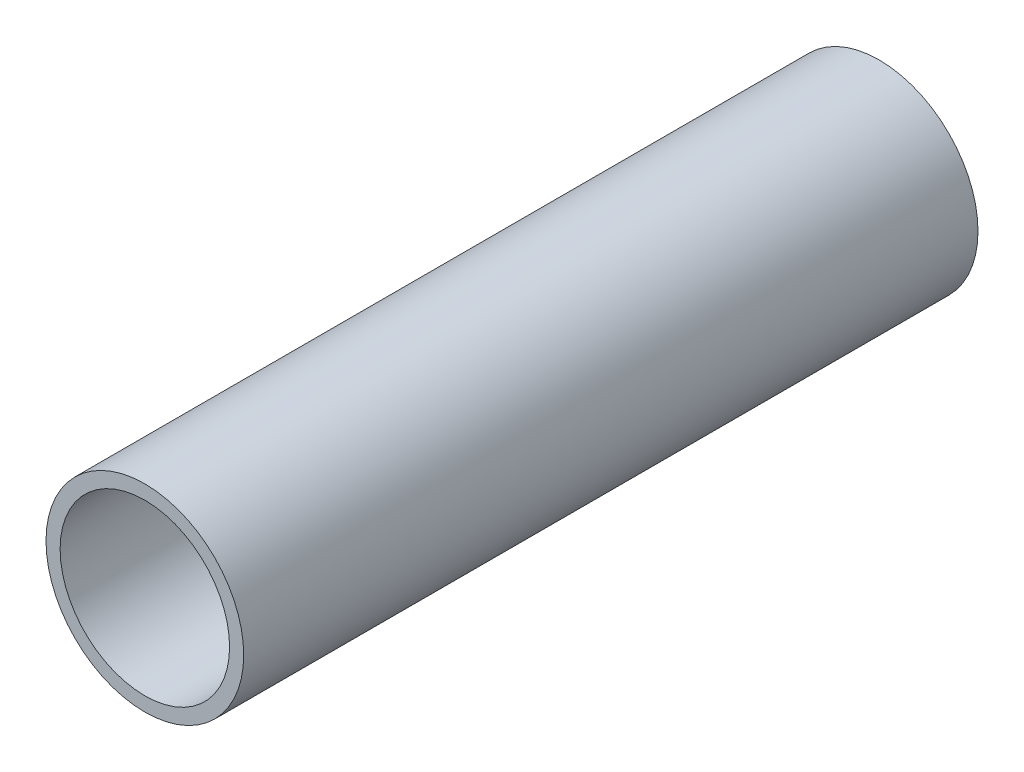
SolidWorks part; units mm, degrees
material "Thornel VCB-20 Carbon Cloth"
ref_plane "Front Plane" through (0, 0, 0) normal (0, 0, 1) x (1, 0, 0)
ref_plane "Top Plane" through (0, 0, 0) normal (0, 1, 0) x (1, 0, 0)
ref_plane "Right Plane" through (0, 0, 0) normal (1, 0, 0) x (0, 0, -1)
sketch "Sketch1" plane through (0, 0, 0) normal (0, 0, 1) x (1, 0, 0)
  circle A0 centre (0, 0) radius 9.525
  circle A1 centre (0, 0) radius 11.1125
  dimension "D1" = 19.05
  dimension "D2" = 22.225
extrude "Boss-Extrude1" add sketch "Sketch1" along normal mid plane 82.55
